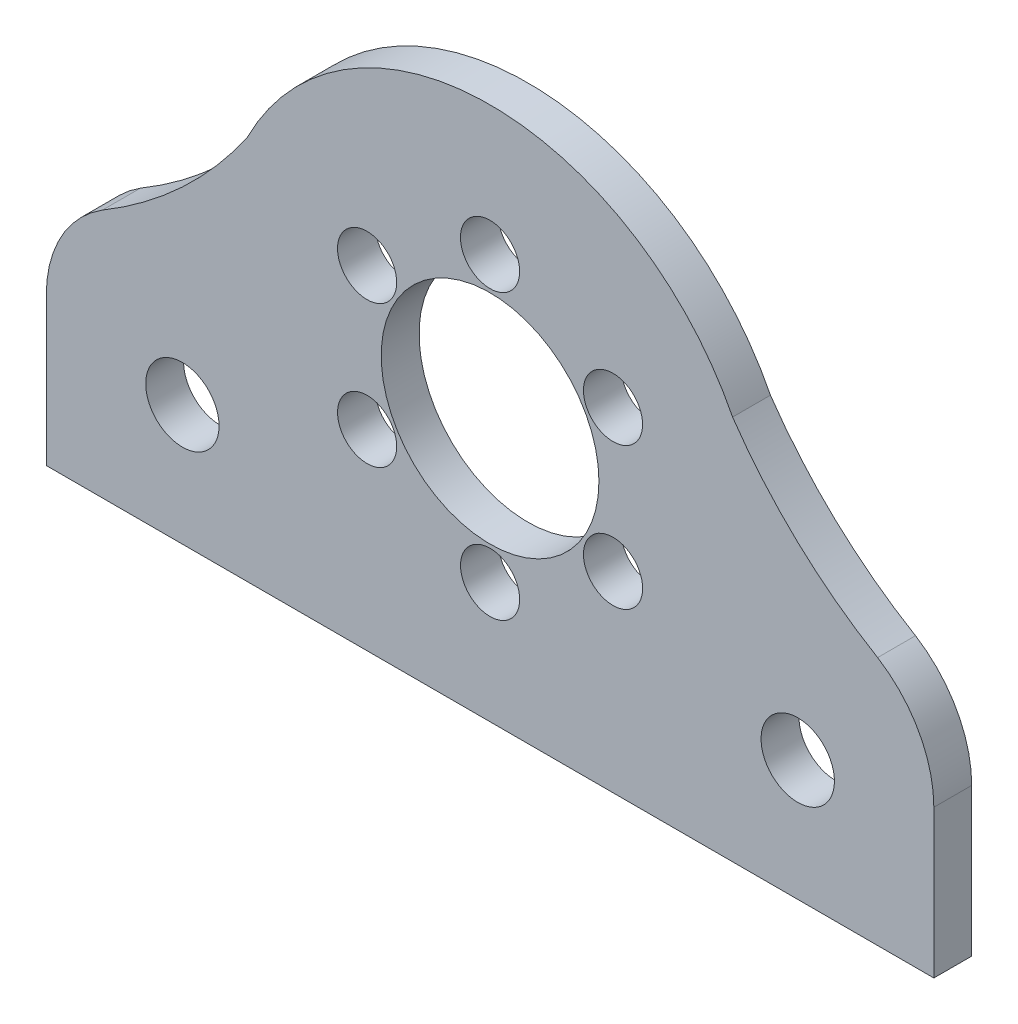
SolidWorks part; units mm, degrees
ref_plane "Alzado" through (0, 0, 0) normal (0, 0, 1) x (1, 0, 0)
ref_plane "Planta" through (0, 0, 0) normal (0, 1, 0) x (1, 0, 0)
ref_plane "Vista lateral" through (0, 0, 0) normal (1, 0, 0) x (0, 0, -1)
sketch "Croquis1" plane through (0, 0, 0) normal (0, 0, 1) x (1, 0, 0)
  line L4 (0, 0) -> (0, 1.5946) construction
  line L17 (-18.75, -11.1) -> (18.75, -11.1)
  line L18 (0, -11.1) -> (0, -9.9022) construction
  line L21 (-18.75, -11.1) -> (-18.75, -4.8527)
  line L23 (18.75, -11.1) -> (18.75, -4.8527)
  line L25 (0, 11.4788) -> (0, -11.1) construction
  circle A8 centre (0, 0) radius 4.6
  circle A12 centre (-0.0012, 5.9988) radius 1.25
  circle A13 centre (5.1945, 3.0004) radius 1.25
  circle A14 centre (5.1957, -2.9984) radius 1.25
  circle A15 centre (0.0012, -5.9988) radius 1.25
  circle A16 centre (-5.1945, -3.0004) radius 1.25
  circle A17 centre (-5.1957, 2.9984) radius 1.25
  circle A19 centre (13, -6) radius 1.55
  circle A21 centre (-13, -6) radius 1.55
  arc A23 (10.2473, 5.1727) -> (-10.2473, 5.1727) centre (0, 0) ccw
  arc A32 (-18.75, -4.8527) -> (-16.3755, -0.5624) centre (-13.6868, -4.8527) cw
  arc A33 (-16.3755, -0.5624) -> (-10.2473, 5.1727) centre (-26.2731, 16.1553) ccw
  arc A34 (16.3755, -0.5624) -> (10.2473, 5.1727) centre (26.2731, 16.1553) cw
  arc A35 (18.75, -4.8527) -> (16.3755, -0.5624) centre (13.6868, -4.8527) ccw
  point P29 (-11.465, -0.5624)
  point P34 (11.465, -0.5624)
  dimension "D1" = 13
  dimension "D2" = 37.5
  dimension "D4" = 6
  dimension "D5" = 11.1
  dimension "D6" = 9.2
  dimension "D9" = 11.4788
extrude "Saliente-Extruir1" add sketch "Croquis1" along normal blind 1.6
